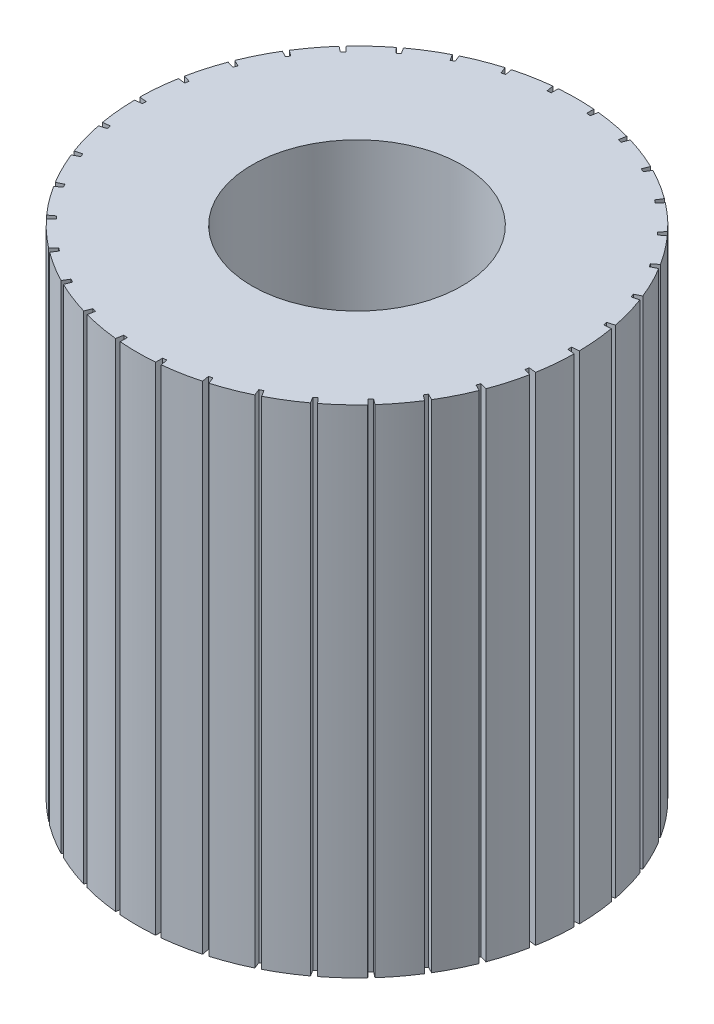
SolidWorks part; units mm, degrees
ref_plane "Front Plane" through (0, 0, 0) normal (0, 0, 1) x (1, 0, 0)
ref_plane "Top Plane" through (0, 0, 0) normal (0, 1, 0) x (1, 0, 0)
ref_plane "Right Plane" through (0, 0, 0) normal (1, 0, 0) x (0, 0, -1)
sketch "Sketch1" plane through (0, 0, 0) normal (0, 1, 0) x (1, 0, 0)
  circle A1 centre (0, 0) radius 15
  dimension "D1" = 30
extrude "Boss-Extrude1" add sketch "Sketch1" along normal blind 35
sketch "Sketch2" plane through (0, 35, 0) normal (0, 1, 0) x (1, 0, 0)
  circle A0 centre (0, 0) radius 7.4
  dimension "D1" = 14.8
extrude "Cut-Extrude1" cut sketch "Sketch2" against normal blind 16.6
ref_plane "Plane2" through (0, 0, 7.4) normal (0, 0, 1) x (1, 0, 0)
sketch "Sketch5" plane through (0, 0, 7.4) normal (0, 0, 1) x (1, 0, 0)
  line L0 (7.4, 35) -> (-7.4, 35) construction
  line L1 (-1.25, 35) -> (1.25, 35)
  line L2 (-1.25, 35) -> (-1.25, 0)
  line L3 (-1.25, 0) -> (1.25, 0)
  line L4 (1.25, 35) -> (1.25, 0)
  line L5 (-15, 0) -> (15, 0) construction
  dimension "D1" = 2.5
extrude "Boss-Extrude4" add sketch "Sketch5" along normal offset from surface (9.554 mm away) 2
pattern_circular "CirPattern1" count 34 over 360 about axis through (0, 0, 0) along (0, 1, 0) of "Boss-Extrude4"
sketch "Sketch6" plane through (0, 35, 0) normal (0, 1, 0) x (1, 0, 0)
  circle A0 centre (0, 0) radius 15.5
  arc A2 (13.9379, -5.5439) -> (14.0351, -5.2929) centre (0, 0) ccw construction
  circle A3 centre (0, 0) radius 17
  dimension "D1" = 0.5
extrude "Cut-Extrude2" cut sketch "Sketch6" against normal through all both and the other way through all
